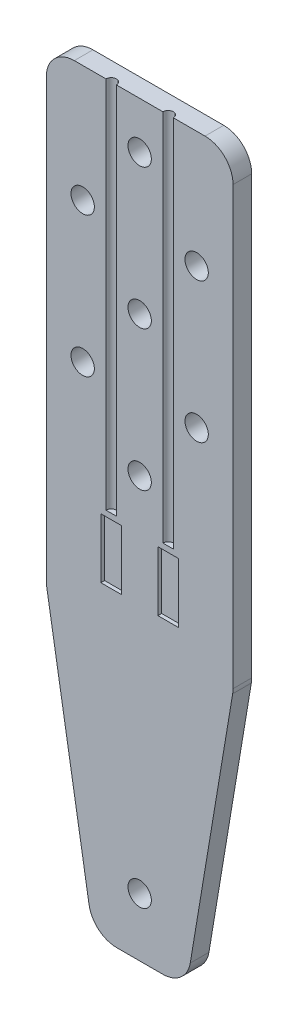
SolidWorks part; units mm, degrees
ref_plane "Front Plane" through (0, 0, 0) normal (0, 0, 1) x (1, 0, 0)
ref_plane "Top Plane" through (0, 0, 0) normal (0, 1, 0) x (1, 0, 0)
ref_plane "Right Plane" through (0, 0, 0) normal (1, 0, 0) x (0, 0, -1)
sketch "Sketch1" plane through (0, 0, 0) normal (0, 0, 1) x (1, 0, 0)
  line L0 (114.3, 63.5) -> (107.95, 25.4) construction
  line L1 (88.9, 63.5) -> (95.25, 25.4) construction
  line L2 (104.713, 67.31) -> (104.713, 158.75) construction
  line L3 (106.237, 67.31) -> (104.713, 67.31) construction
  line L4 (106.237, 158.75) -> (106.237, 67.31) construction
  line L5 (104.713, 158.75) -> (106.237, 158.75) construction
  line L6 (99.125, 127) -> (111.825, 127) construction
  line L7 (104.078, 67.31) -> (104.078, 77.47) construction
  line L8 (106.872, 67.31) -> (104.078, 67.31) construction
  line L9 (106.872, 77.47) -> (106.872, 67.31) construction
  line L10 (104.078, 77.47) -> (106.872, 77.47) construction
  line L11 (96.328, 67.31) -> (96.328, 77.47) construction
  line L12 (99.122, 67.31) -> (96.328, 67.31) construction
  line L13 (99.122, 77.47) -> (99.122, 67.31) construction
  line L14 (96.328, 77.47) -> (99.122, 77.47) construction
  line L15 (114.3, 25.4) -> (114.3, 127) construction
  line L16 (88.9, 25.4) -> (114.3, 25.4) construction
  line L17 (88.9, 127) -> (88.9, 25.4) construction
  line L18 (114.3, 127) -> (88.9, 127) construction
  line L19 (109.35, 127) -> (109.35, 25.4) construction
  line L20 (93.85, 127) -> (93.85, 25.4) construction
  line L21 (96.963, 67.31) -> (96.963, 158.75) construction
  line L22 (98.487, 67.31) -> (96.963, 67.31) construction
  line L23 (98.487, 158.75) -> (98.487, 67.31) construction
  line L24 (96.963, 158.75) -> (98.487, 158.75) construction
  line L25 (91.375, 127) -> (104.075, 127) construction
  line L26 (101.6, 127) -> (101.6, 25.4) construction
  line L27 (105.475, 127) -> (97.725, 127) construction
  line L28 (88.9, 127) -> (88.9, 63.5)
  line L29 (88.9, 63.5) -> (95.25, 25.4)
  line L30 (95.25, 25.4) -> (107.95, 25.4)
  line L31 (107.95, 25.4) -> (114.3, 63.5)
  line L32 (114.3, 63.5) -> (114.3, 127)
  line L33 (114.3, 127) -> (88.9, 127)
  circle A0 centre (93.85, 92.075) radius 1.5875 construction
  circle A1 centre (109.35, 92.075) radius 1.5875 construction
  circle A2 centre (93.85, 111.125) radius 1.5875 construction
  circle A3 centre (109.35, 111.125) radius 1.5875 construction
  circle A4 centre (101.6, 82.55) radius 1.5875 construction
  circle A5 centre (101.6, 101.6) radius 1.5875 construction
  circle A6 centre (101.6, 120.65) radius 1.5875 construction
  circle A7 centre (97.725, 127) radius 0.762 construction
  circle A8 centre (105.475, 127) radius 0.762 construction
extrude "Extrude1" add sketch "Sketch1" against normal blind 2.54
sketch "Sketch2" plane through (0, 0, 0) normal (0, 0, 1) x (1, 0, 0)
  circle A0 centre (93.85, 111.125) radius 1.5875
  circle A1 centre (101.6, 120.65) radius 1.5875
  circle A2 centre (109.35, 111.125) radius 1.5875
  circle A3 centre (101.6, 101.6) radius 1.5875
  circle A4 centre (93.85, 92.075) radius 1.5875
  circle A5 centre (109.35, 92.075) radius 1.5875
  circle A6 centre (101.6, 82.55) radius 1.5875
extrude "Cut-Extrude1" cut sketch "Sketch2" against normal up to surface (2.54 mm away) up to face at (101.6, 71.9667, -2.54)
sketch "Sketch3" plane through (0, 0, 0) normal (0, 0, 1) x (1, 0, 0)
  line L1 (96.328, 75.438) -> (99.122, 75.438)
  line L2 (96.328, 75.438) -> (96.328, 67.31)
  line L3 (96.328, 67.31) -> (99.122, 67.31)
  line L4 (99.122, 75.438) -> (99.122, 67.31)
  line L5 (104.078, 75.438) -> (106.872, 75.438)
  line L6 (104.078, 75.438) -> (104.078, 67.31)
  line L7 (104.078, 67.31) -> (106.872, 67.31)
  line L8 (106.872, 75.438) -> (106.872, 67.31)
extrude "Cut-Extrude2" cut sketch "Sketch3" against normal blind 0.508
sketch "Sketch4" plane through (0, 127, 0) normal (0, 1, 0) x (1, 0, 0)
  circle A0 centre (97.725, 0) radius 0.7112
  circle A1 centre (105.475, 0) radius 0.7112
extrude "Cut-Extrude3" cut sketch "Sketch4" against normal blind 50.8
fillet "Fillet1" radius 3.81 6 edges at (114.3, 127, -1.27) (107.95, 25.4, -1.27) (114.3, 63.5, -1.27) (95.25, 25.4, -1.27) (88.9, 63.5, -1.27) (88.9, 127, -1.27)
sketch "Sketch5" plane through (0, 0, 0) normal (0, 0, 1) x (1, 0, 0)
  line L0 (101.6, 25.4) -> (101.6, 33.3375) construction
  line L1 (101.6, 127) -> (101.6, 25.4) construction
  circle A0 centre (101.6, 33.3375) radius 1.5875
extrude "Cut-Extrude4" cut sketch "Sketch5" against normal up to surface (2.54 mm away) up to face at (103.1875, 82.55, -2.54)
